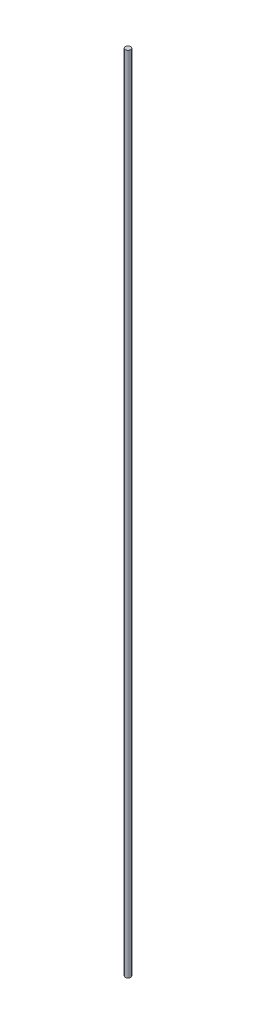
SolidWorks part; units mm, degrees
material "3.1655 (EN AW-2011)"
ref_plane "Plano frontal" through (0, 0, 0) normal (0, 0, 1) x (1, 0, 0)
ref_plane "Plano superior" through (0, 0, 0) normal (0, 1, 0) x (1, 0, 0)
ref_plane "Plano direito" through (0, 0, 0) normal (1, 0, 0) x (0, 0, -1)
sketch "Esboço2" plane through (0, 0, 0) normal (0, 1, 0) x (1, 0, 0)
  circle A0 centre (0, 0) radius 1
  dimension "D1" = 2
extrude "Ressalto-extrusão1" add sketch "Esboço2" along normal blind 300
